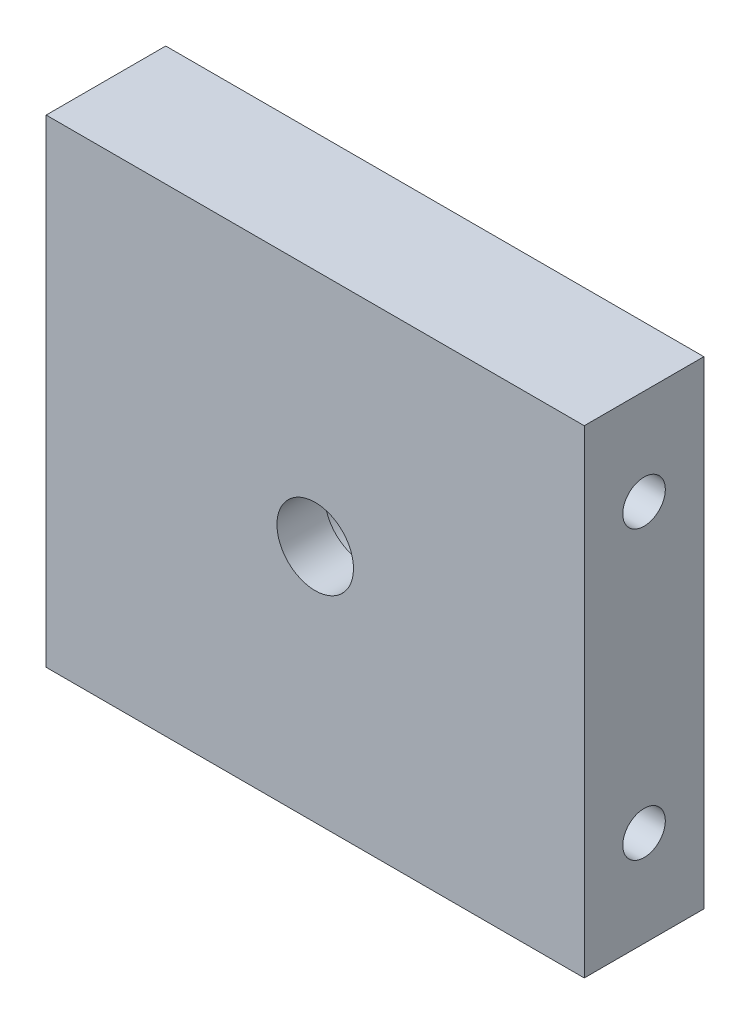
SolidWorks part; units mm, degrees
ref_plane "Front Plane" through (0, 0, 0) normal (0, 0, 1) x (1, 0, 0)
ref_plane "Top Plane" through (0, 0, 0) normal (0, 1, 0) x (1, 0, 0)
ref_plane "Right Plane" through (0, 0, 0) normal (1, 0, 0) x (0, 0, -1)
sketch "Sketch2" plane through (0, 0, 0) normal (0, 0, 1) x (1, 0, 0)
  line L1 (-14.2875, -12.7) -> (14.2875, -12.7)
  line L2 (-14.2875, -12.7) -> (-14.2875, 12.7)
  line L3 (-14.2875, 12.7) -> (14.2875, 12.7)
  line L4 (14.2875, -12.7) -> (14.2875, 12.7)
  line L5 (-14.2875, -12.7) -> (14.2875, 12.7) construction
  line L6 (-14.2875, 12.7) -> (14.2875, -12.7) construction
  point P0 (0, 0)
  dimension "D1" = 28.575
  dimension "D2" = 25.4
extrude "Boss-Extrude1" add sketch "Sketch2" along normal blind 6.35
hole_wizard "#4-40 Tapped Hole2" positions "Sketch4" profile "Sketch3" tap size "#4-40" standard "ANSI Inch"
sketch "Sketch4" plane through (14.2875, 0, 0) normal (1, 0, 0) x (0, 0, -1)
  line L0 (-3.175, 12.7) -> (-3.175, -12.7) construction
  line L1 (-6.35, 12.7) -> (0, 12.7) construction
  line L2 (-6.35, -12.7) -> (0, -12.7) construction
  point P9 (-3.175, 7.62)
  point P11 (-3.175, -7.62)
  dimension "D1" = 7.62
  dimension "D2" = 7.62
sketch "Sketch3" plane through (14.2875, 7.62, 3.175) normal (0, 1, 0) x (0, 0, -1)
  line L0 (0, 0) -> (0, 8.2992)
  line L1 (0, 8.2992) -> (1.1303, 7.62)
  line L2 (1.1303, 7.62) -> (1.1303, 0)
  line L5 (1.1303, 0) -> (0, 0)
  line L10 (0, 8.2992) -> (-1.1303, 7.62) construction
  line L11 (0, -6.35) -> (0, 107.95) construction
  dimension "Tap Drill Dia." = 2.2606
  dimension "Tap Drill Depth" = 7.62
  dimension "Drill Angle" = 118
cosmetic thread "Hole Thread1" parameters "D1"=5.588, "D2"=2.8448
cosmetic thread "Hole Thread2" parameters "D1"=5.588, "D2"=2.8448
hole_wizard "#4-40 Tapped Hole1" positions "Sketch6" profile "Sketch5" tap size "#4-40" standard "ANSI Inch"
sketch "Sketch6" plane through (-14.2875, 0, 0) normal (-1, 0, 0) x (0, 0, 1)
  line L0 (3.175, 12.7) -> (3.175, -12.7) construction
  line L1 (6.35, 12.7) -> (0, 12.7) construction
  line L2 (6.35, -12.7) -> (0, -12.7) construction
  line L3 (0, 12.7) -> (0, -12.7) construction
  point P8 (3.175, 7.62)
  point P10 (3.175, -7.62)
  point P13 (0, 0)
  point P16 (0, 0)
  dimension "D1" = 7.62
  dimension "D2" = 7.62
sketch "Sketch5" plane through (-14.2875, 7.62, 3.175) normal (0, 1, 0) x (0, 0, 1)
  line L0 (0, 0) -> (0, 8.2992)
  line L1 (0, 8.2992) -> (1.1303, 7.62)
  line L2 (1.1303, 7.62) -> (1.1303, 0)
  line L5 (1.1303, 0) -> (0, 0)
  line L10 (0, 8.2992) -> (-1.1303, 7.62) construction
  line L11 (0, -6.35) -> (0, 107.95) construction
  dimension "Tap Drill Dia." = 2.2606
  dimension "Tap Drill Depth" = 7.62
  dimension "Drill Angle" = 118
cosmetic thread "Hole Thread3" parameters "D1"=5.588, "D2"=2.8448
cosmetic thread "Hole Thread4" parameters "D1"=5.588, "D2"=2.8448
sketch "Sketch7" plane through (0, 0, 6.35) normal (0, 0, 1) x (1, 0, 0)
  line L1 (0.8457, -1.3629) -> (1.6031, 0.0509) construction
  line L2 (1.6031, 0.0509) -> (0.7575, 1.4138) construction
  line L3 (0.7575, 1.4138) -> (-0.8457, 1.3629) construction
  line L4 (-0.8457, 1.3629) -> (-1.6031, -0.0509) construction
  line L5 (-1.6031, -0.0509) -> (-0.7575, -1.4138) construction
  line L6 (-0.7575, -1.4138) -> (0.8457, -1.3629) construction
  circle A0 centre (0, 0) radius 2.032
  circle A1 centre (0, 0) radius 1.3891 construction
  dimension "D2" = 4.064
  dimension "D1" = 2.7781
extrude "Cut-Extrude1" cut sketch "Sketch7" against normal blind 2.54
sketch "Sketch12" plane through (0, 0, 0) normal (0, 0, -1) x (-1, 0, 0)
  circle A0 centre (0, 0) radius 3.048
  dimension "D1" = 6.096
extrude "Cut-Extrude2" cut sketch "Sketch12" against normal up to surface (3.81 mm away) up to face at (2.032, 0, 3.81)
